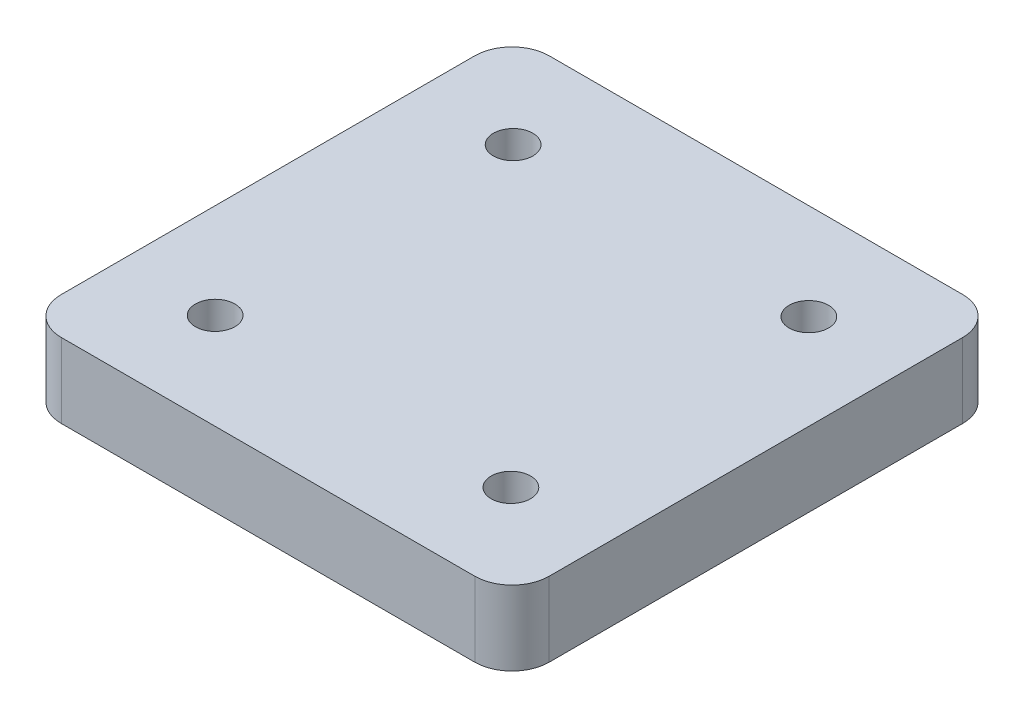
SolidWorks part; units mm, degrees
ref_plane "Front Plane" through (0, 0, 0) normal (0, 0, 1) x (1, 0, 0)
ref_plane "Top Plane" through (0, 0, 0) normal (0, 1, 0) x (1, 0, 0)
ref_plane "Right Plane" through (0, 0, 0) normal (1, 0, 0) x (0, 0, -1)
sketch "Sketch2" plane through (0, 0, 0) normal (0, 1, 0) x (1, 0, 0)
  line L1 (-27.75, -32.75) -> (27.75, -32.75)
  line L2 (-32.75, -27.75) -> (-32.75, 27.75)
  line L3 (-27.75, 32.75) -> (27.75, 32.75)
  line L4 (32.75, -27.75) -> (32.75, 27.75)
  circle A0 centre (-19.85, 20) radius 2.65
  circle A1 centre (20, 19.85) radius 2.65
  circle A2 centre (19.85, -20) radius 2.65
  circle A3 centre (-20, -19.85) radius 2.65
  arc A4 (27.75, 32.75) -> (32.75, 27.75) centre (27.75, 27.75) cw
  arc A5 (27.75, -32.75) -> (32.75, -27.75) centre (27.75, -27.75) ccw
  arc A6 (-27.75, -32.75) -> (-32.75, -27.75) centre (-27.75, -27.75) cw
  arc A7 (-32.75, 27.75) -> (-27.75, 32.75) centre (-27.75, 27.75) cw
  point P0 (0, 0)
  point P6 (0, -0.2184)
  point P10 (32.75, 32.75)
  point P20 (0, 0)
  point P23 (-32.75, -32.75)
  point P26 (-32.75, 32.75)
  dimension "D6" = 5.3
  dimension "D3" = 5
  dimension "D1" = 65.5
  dimension "D2" = 65.5
  dimension "D4" = 32.75
  dimension "D5" = 32.75
  dimension "D8" = 19.85
  dimension "D9" = 20
  dimension "D7" = 4
extrude "Boss-Extrude1" add sketch "Sketch2" along normal blind 10
